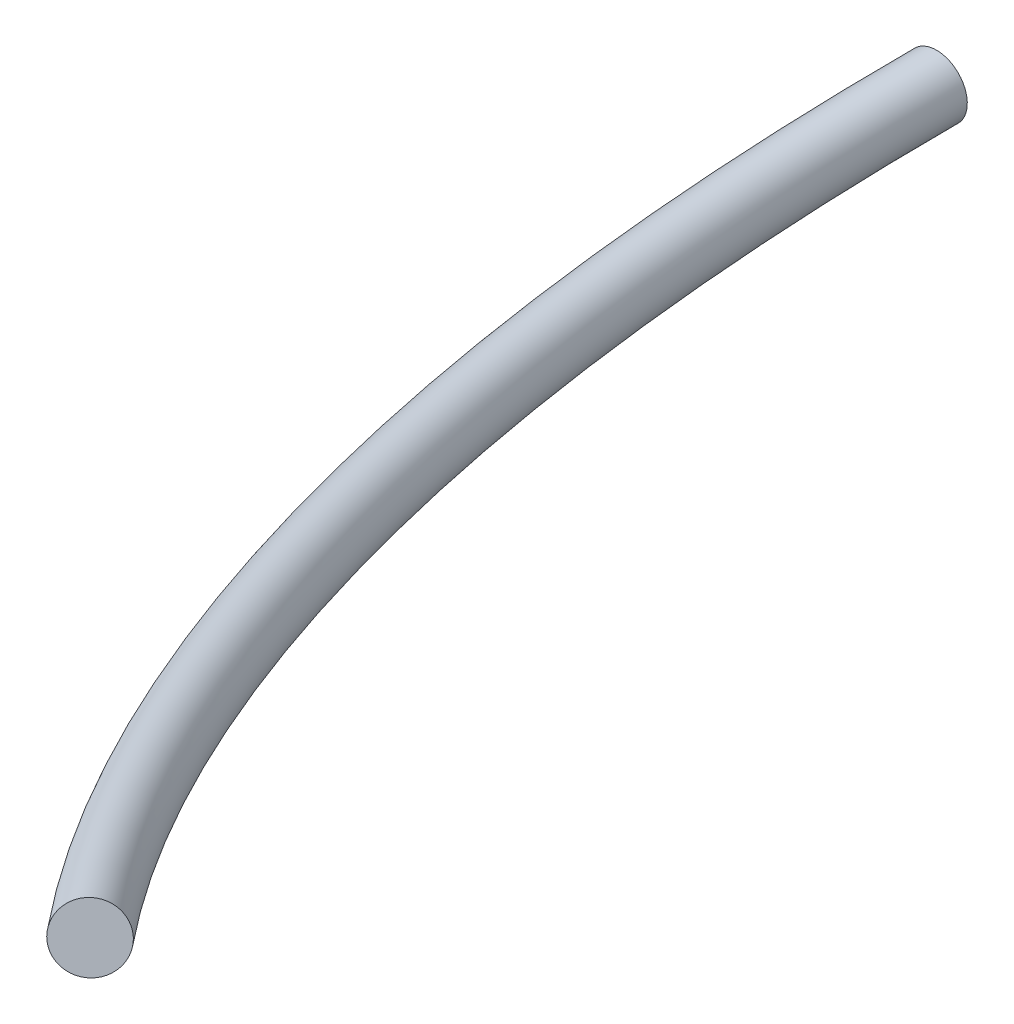
SolidWorks part; units mm, degrees
ref_plane "Front" through (0, 0, 0) normal (0, 0, 1) x (1, 0, 0)
ref_plane "Top" through (0, 0, 0) normal (0, 1, 0) x (1, 0, 0)
ref_plane "Right" through (0, 0, 0) normal (1, 0, 0) x (0, 0, -1)
sketch "Sketch1" plane through (0, 0, 0) normal (0, 0, 1) x (1, 0, 0)
  circle A0 centre (-7476.5073, -13776.5668) radius 50.8
ref_plane "Plane1" through (3544.9554, -9782.7358, 0) normal (-0.3407, 0.9402, 0) x (0.786, 0.2848, 0.5487)
sketch "Sketch2" plane through (3544.9554, -9782.7358, 0) normal (-0.3407, 0.9402, 0) x (0.786, 0.2848, 0.5487)
  line L0 (-7857.3652, -7809.6655) -> (-6230.5539, -8213.6389) construction
  line L1 (-9800.6926, -6431.9323) -> (-9243.1952, -7281.422) construction
  arc A0 (-9800.6926, -6431.9323) -> (-7857.3652, -7809.6655) centre (-7070.275, -4640.0323) ccw
  point P3 (-8065.0296, -7750.7475)
  point P5 (-8800.5932, -7409.8851)
  point P6 (-9429.5351, -6898.3452)
  dimension "D1" = 2438.4
  dimension "D2" = 215.9
  dimension "D3" = 812.8
  dimension "D4" = 812.8
sweep "Sweep1" add profiles "Sketch1" path "Sketch2"
